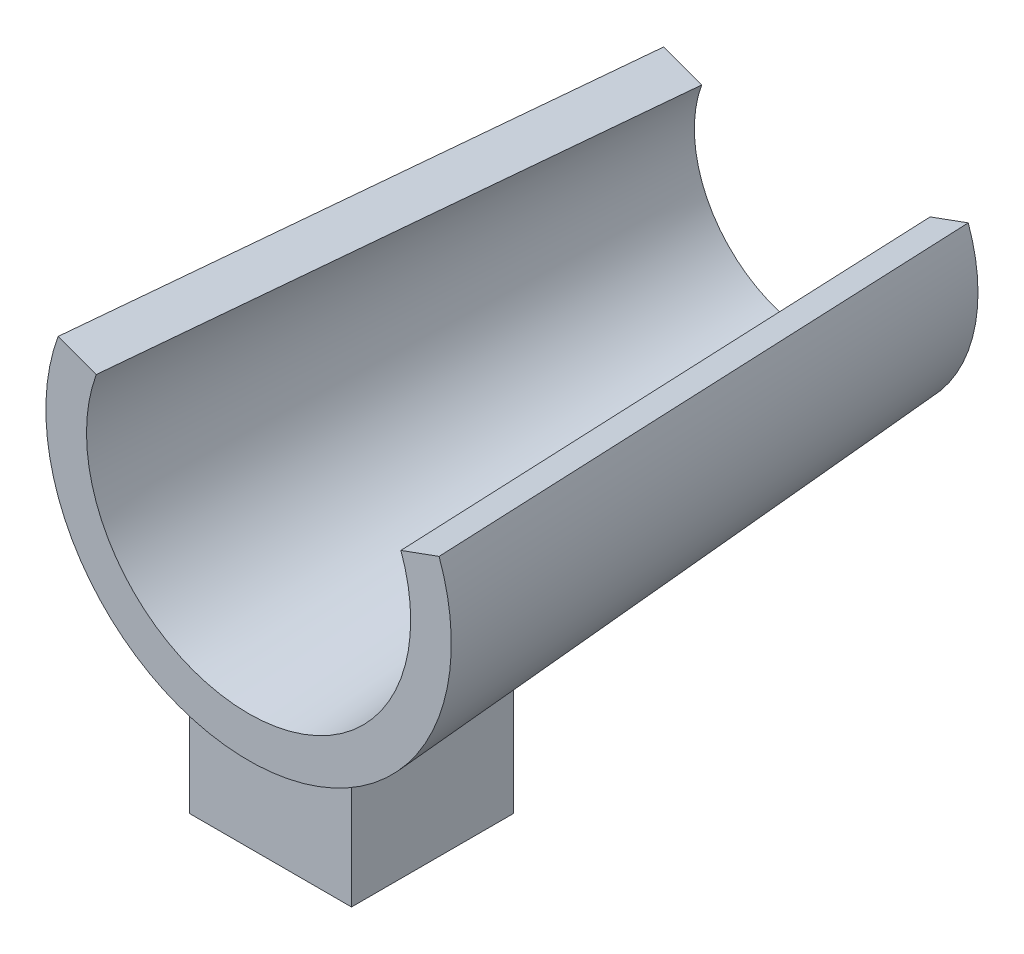
SolidWorks part; units mm, degrees
ref_plane "Front Plane" through (0, 0, 0) normal (0, 0, 1) x (1, 0, 0)
ref_plane "Top Plane" through (0, 0, 0) normal (0, 1, 0) x (1, 0, 0)
ref_plane "Right Plane" through (0, 0, 0) normal (1, 0, 0) x (0, 0, -1)
sketch "Sketch1" plane through (0, 0, 0) normal (0, 1, 0) x (1, 0, 0)
  line L1 (-50.8, 88.9) -> (-38.1, 88.9) construction
  line L2 (-50.8, 88.9) -> (-50.8, -88.9) construction
  line L4 (50.8, 88.9) -> (50.8, -88.9) construction
  line L5 (-50.8, 88.9) -> (50.8, -88.9) construction
  line L6 (-50.8, -88.9) -> (50.8, 88.9) construction
  line L7 (38.1, 88.9) -> (50.8, -88.9)
  line L9 (-50.8, -88.9) -> (-38.1, 88.9)
  line L10 (-50.8, 88.9) -> (-63.5324, -88.9)
  line L12 (0, 0) -> (0, 88.9) construction
  line L17 (-38.1, 88.9) -> (-50.8, 88.9)
  line L18 (38.1, 88.9) -> (50.8, 88.9)
  line L19 (-50.8, -88.9) -> (-63.5324, -88.9)
  line L20 (50.8, -88.9) -> (63.5324, -88.9)
  line L21 (50.8, 88.9) -> (63.5324, -88.9)
  line L22 (38.1, 88.9) -> (50.8, 88.9) construction
  point P0 (0, 0)
revolve "Revolve1" add sketch "Sketch1" angle 200 about L12
ref_plane "Plane1" through (0, -63.5324, 0) normal (0, 1, 0) x (1, 0, 0)
sketch "Sketch2" plane through (0, -63.5324, 0) normal (0, 1, 0) x (1, 0, 0)
  line L0 (0, -46.8939) -> (0, 46.8939) construction
  line L1 (-25.4, -31.2461) -> (25.4, -31.2461)
  line L2 (-25.4, -31.2461) -> (-25.4, -82.0461)
  line L3 (-25.4, -82.0461) -> (25.4, -82.0461)
  line L4 (25.4, -31.2461) -> (25.4, -82.0461)
  line L5 (-25.4, -31.2461) -> (25.4, -82.0461) construction
  line L6 (-25.4, -82.0461) -> (25.4, -31.2461) construction
  point P0 (0, -56.6461)
extrude "Boss-Extrude1" add sketch "Sketch2" along normal up to surface and the other way blind 30.48 up to face at (0, -18.8071, 0)
ref_plane "Plane2" through (0, 0, 56.6461) normal (0, 0, 1) x (1, 0, 0)
sketch "Sketch3" plane through (0, 0, 56.6461) normal (0, 0, 1) x (1, 0, 0)
  line L0 (0, -71.9793) -> (0, 71.9793) construction
  line L1 (-25.4, -94.0124) -> (25.4, -94.0124) construction
  line L2 (0, -78.1501) -> (0, -109.1421) construction
  line L3 (0, -57.8301) -> (0, -98.4701)
  arc A0 (0, -57.8301) -> (0, -98.4701) centre (0, -78.1501) ccw
  point P4 (-12.7, -94.0124)
  point P5 (12.7, -94.0124)
  dimension "D1" = 40.64
  dimension "D2" = 25.4
revolve "Cut-Revolve2" cut sketch "Sketch3" angle 360 about L2
